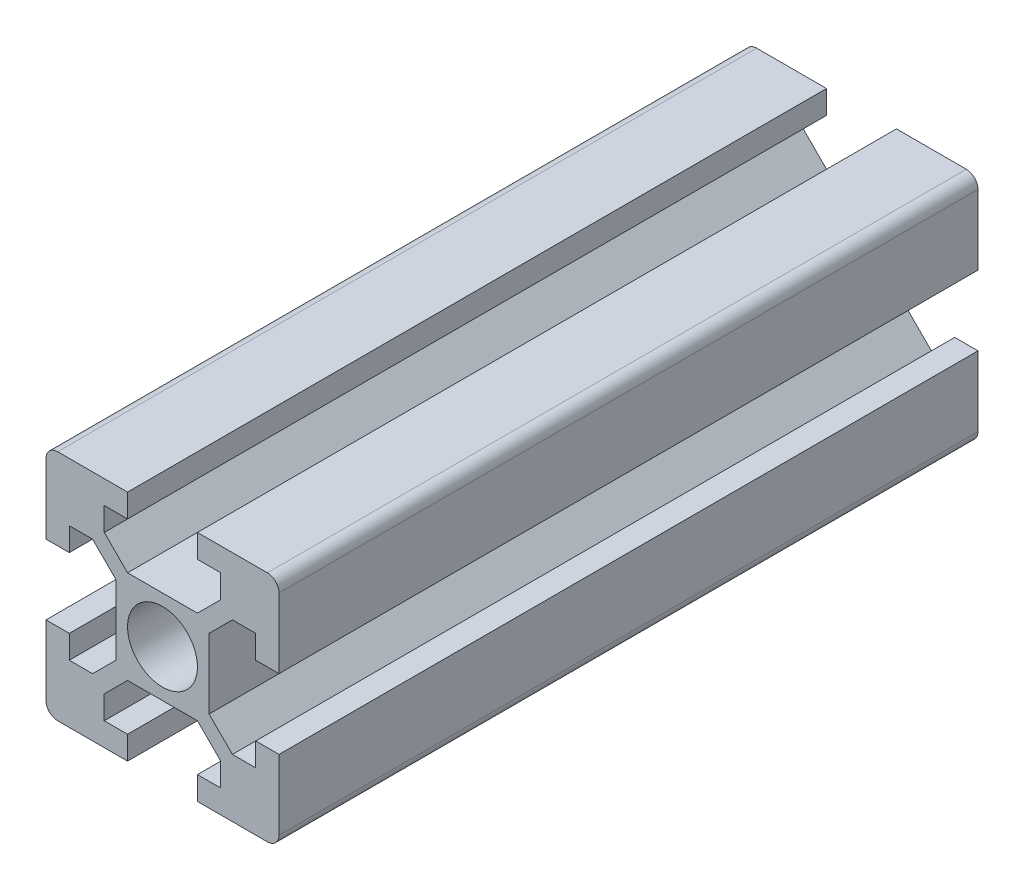
SolidWorks part; units mm, degrees
ref_plane "前视基准面" through (0, 0, 0) normal (0, 0, 1) x (1, 0, 0)
ref_plane "上视基准面" through (0, 0, 0) normal (0, 1, 0) x (1, 0, 0)
ref_plane "右视基准面" through (0, 0, 0) normal (1, 0, 0) x (0, 0, -1)
other "Configuration Table"
sketch "草图1" plane through (0, 0, 0) normal (0, 0, 1) x (1, 0, 0)
  line L0 (-0.3614, 1.4315) -> (23483.3566, 1.4315) construction
  line L1 (0, 0) -> (0, 23483.718) construction
  line L2 (-10, 4.4315) -> (-8, 4.4315)
  line L3 (-10, 11.4315) -> (10, 11.4315)
  line L4 (-10, 11.4315) -> (-10, -8.5685)
  line L5 (-10, -8.5685) -> (10, -8.5685)
  line L6 (10, 11.4315) -> (10, -8.5685)
  line L7 (-4, 5.4315) -> (4, 5.4315)
  line L8 (-4, 5.4315) -> (-4, -2.5685)
  line L9 (-4, -2.5685) -> (4, -2.5685)
  line L10 (4, 5.4315) -> (4, -2.5685)
  line L11 (-8, 4.4315) -> (-8, 6.4315)
  line L12 (-8, 6.4315) -> (-6, 6.4315)
  line L13 (-10, 4.4315) -> (-10, 1.4315)
  line L14 (0, 1.4315) -> (-35355.3391, 35356.7705) construction
  line L15 (0, 1.4315) -> (35355.3391, 35356.7705) construction
  line L16 (-6, 6.4315) -> (-4, 4.4315)
  line L17 (-10, 4.4315) -> (-10, 11.4315)
  line L18 (-4, 5.4315) -> (-10, 11.4315)
  line L19 (-5, 7.4315) -> (-3, 5.4315)
  line L20 (-5, 9.4315) -> (-5, 7.4315)
  line L21 (-3, 9.4315) -> (-5, 9.4315)
  line L22 (-3, 11.4315) -> (-3, 9.4315)
  line L23 (-6, -3.5685) -> (-4, -1.5685)
  line L24 (-8, -3.5685) -> (-6, -3.5685)
  line L25 (-10, 11.4315) -> (10, 11.4315)
  line L26 (-10, -8.5685) -> (10, -8.5685)
  line L27 (-8, -1.5685) -> (-8, -3.5685)
  line L28 (-10, -1.5685) -> (-8, -1.5685)
  line L29 (-5, -4.5685) -> (-3, -2.5685)
  line L30 (-5, -6.5685) -> (-5, -4.5685)
  line L31 (-3, -6.5685) -> (-5, -6.5685)
  line L32 (-3, -8.5685) -> (-3, -6.5685)
  line L33 (3, -8.5685) -> (3, -6.5685)
  line L34 (3, -6.5685) -> (5, -6.5685)
  line L35 (5, -6.5685) -> (5, -4.5685)
  line L36 (5, -4.5685) -> (3, -2.5685)
  line L37 (6, -3.5685) -> (4, -1.5685)
  line L38 (8, -3.5685) -> (6, -3.5685)
  line L39 (8, -1.5685) -> (8, -3.5685)
  line L40 (10, -1.5685) -> (8, -1.5685)
  line L41 (10, 4.4315) -> (8, 4.4315)
  line L42 (8, 4.4315) -> (8, 6.4315)
  line L43 (8, 6.4315) -> (6, 6.4315)
  line L44 (6, 6.4315) -> (4, 4.4315)
  line L45 (5, 7.4315) -> (3, 5.4315)
  line L46 (5, 9.4315) -> (5, 7.4315)
  line L47 (3, 9.4315) -> (5, 9.4315)
  line L48 (-10, 11.4315) -> (-10, -8.5685)
  line L49 (10, 11.4315) -> (10, -8.5685)
  line L50 (3, 11.4315) -> (3, 9.4315)
  circle A0 centre (0, 1.4315) radius 3
  dimension "D2" = 6
  dimension "D1" = 20
  dimension "D3" = 8
  dimension "D4" = 8
  dimension "D5" = 3
  dimension "D6" = 2
  dimension "D7" = 2
  dimension "D8" = 2
extrude "凸台-拉伸1" add sketch "草图1" along normal blind 60 contours L25 L50 L47 L46 L45 L7 L10 L44 L43 L42 L41 L6 | L6 L40 L39 L38 L37 L10 L9 L36 L35 L34 L33 L5 | L5 L32 L31 L30 L29 L9 L8 L23 L24 L27 L28 L4 | L22 L3 L18 L7 L19 L20 L21 | L8 L18 L4 L2 L11 L12 L16 | L10 L7 L8 L9 A0
fillet "圆角2" radius 1 4 edges at (10, 11.4315, 30) (10, -8.5685, 30) (-10, -8.5685, 30) (-10, 11.4315, 30)
